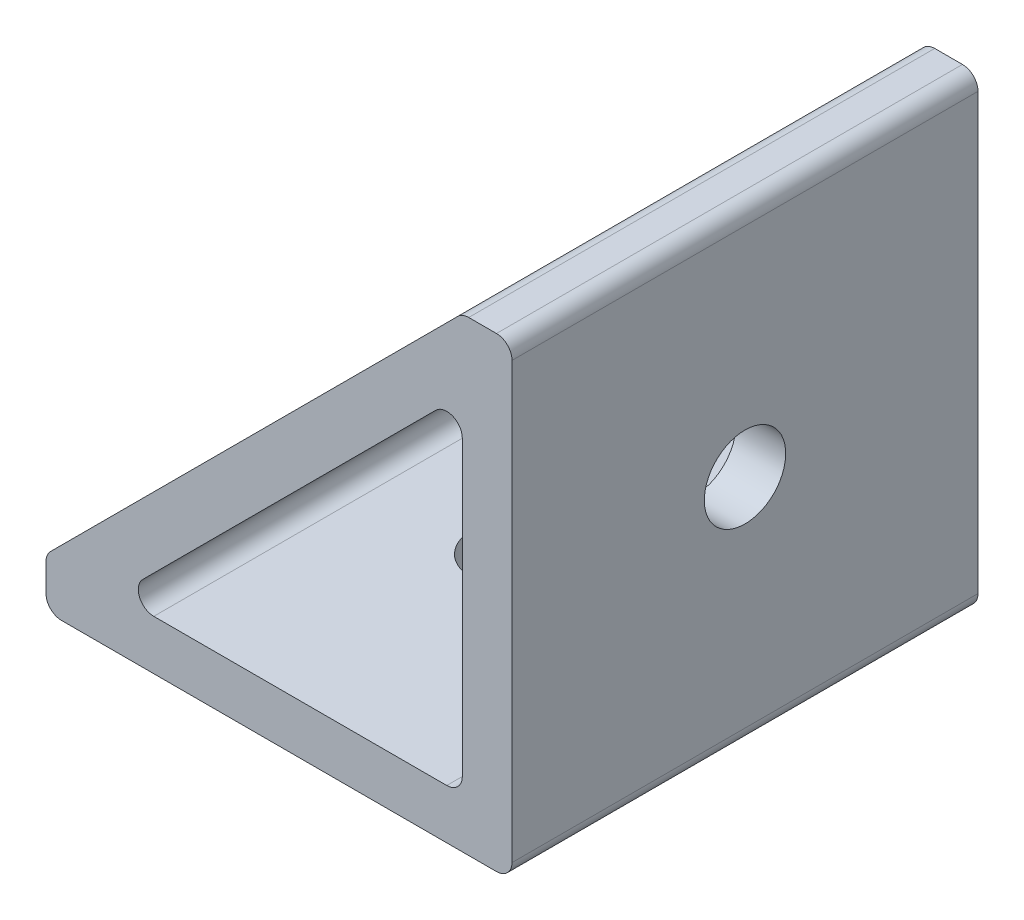
SolidWorks part; units mm, degrees
ref_plane "Front Plane" through (0, 0, 0) normal (0, 0, 1) x (1, 0, 0)
ref_plane "Top Plane" through (0, 0, 0) normal (0, 1, 0) x (1, 0, 0)
ref_plane "Right Plane" through (0, 0, 0) normal (1, 0, 0) x (0, 0, -1)
sketch "Sketch1" plane through (0, 0, 0) normal (0, 0, 1) x (1, 0, 0)
  line L0 (0, 0) -> (0, 38.1)
  line L1 (0, 38.1) -> (-4.064, 38.1)
  line L2 (-4.064, 38.1) -> (-38.1, 4.064)
  line L3 (-38.1, 4.064) -> (-38.1, 0)
  line L4 (-38.1, 0) -> (0, 0)
  line L5 (-32.3526, 4.064) -> (-4.064, 4.064)
  line L6 (-4.064, 4.064) -> (-4.064, 32.3526)
  line L7 (-4.064, 32.3526) -> (-32.3526, 4.064)
  dimension "D1" = 4.064
  dimension "D2" = 4.064
  dimension "D3" = 4.064
  dimension "D4" = 38.1
  dimension "D5" = 38.1
extrude "Boss-Extrude1" add sketch "Sketch1" along normal mid plane 38.1
sketch "Sketch3" plane through (0, 0, 0) normal (1, 0, 0) x (0, 0, -1)
  line L0 (-19.05, 0) -> (-19.05, 38.1) construction
  circle A0 centre (0, 19.05) radius 3.3274
  point P2 (0, 0)
  point P4 (0, 0)
  point P6 (0, 0)
  point P9 (-19.05, 19.05)
  dimension "D1" = 6.6548
extrude "Cut-Extrude2" cut sketch "Sketch3" against normal up to next
sketch "Sketch4" plane through (0, 0, 0) normal (0, -1, 0) x (1, 0, 0)
  line L0 (-38.1, 19.05) -> (0, 19.05) construction
  circle A0 centre (-19.05, 0) radius 3.3274
  point P2 (0, 0)
  point P6 (-19.05, 19.05)
  dimension "D1" = 6.6548
extrude "Cut-Extrude3" cut sketch "Sketch4" against normal up to next
sketch "Sketch2" plane through (-21.082, 21.082, 0) normal (-0.7071, 0.7071, 0) x (0, 0, 1)
  line L14 (11.43, 16.4471) -> (-11.43, 16.4471)
  line L15 (11.43, -16.4471) -> (11.43, 16.4471)
  line L16 (-11.43, -16.4471) -> (11.43, -16.4471)
  line L17 (-11.43, 16.4471) -> (-11.43, -16.4471)
  line L18 (3.81, 16.4471) -> (-3.81, 16.4471)
  line L19 (11.43, -8.8271) -> (11.43, 8.8271)
  line L20 (-3.81, -16.4471) -> (3.81, -16.4471)
  line L21 (-11.43, 8.8271) -> (-11.43, -8.8271)
  arc A0 (11.43, 8.8271) -> (3.81, 16.4471) centre (3.81, 8.8271) ccw
  arc A1 (-11.43, 8.8271) -> (-3.81, 16.4471) centre (-3.81, 8.8271) cw
  arc A2 (-11.43, -8.8271) -> (-3.81, -16.4471) centre (-3.81, -8.8271) ccw
  arc A3 (11.43, -8.8271) -> (3.81, -16.4471) centre (3.81, -8.8271) cw
  dimension "D2" = 7.62
  dimension "D1" = 7.62
extrude "Cut-Extrude1" cut sketch "Sketch2" against normal up to next
fillet "Fillet1" radius 1.27 8 edges at (0, 38.1, 0) (-4.064, 38.1, 0) (-38.1, 4.064, 0) (-38.1, 0, 0) (0, 0, 0) (-4.064, 32.3526, 0) (-4.064, 4.064, 0) (-32.3526, 4.064, 0)
